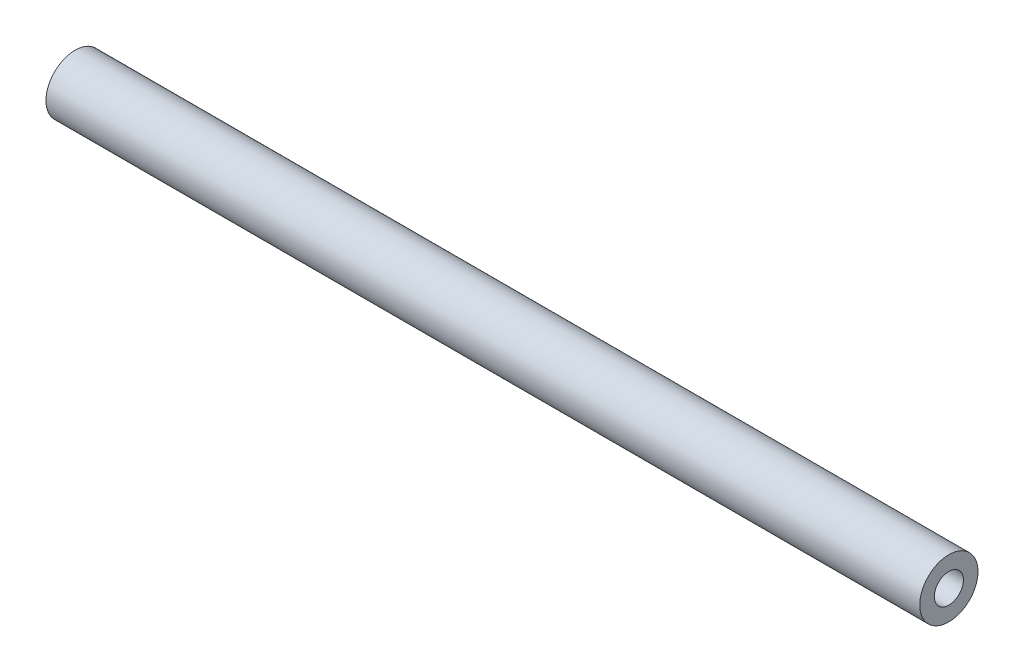
SolidWorks part; units mm, degrees
ref_plane "Front Plane" through (0, 0, 0) normal (0, 0, 1) x (1, 0, 0)
ref_plane "Top Plane" through (0, 0, 0) normal (0, 1, 0) x (1, 0, 0)
ref_plane "Right Plane" through (0, 0, 0) normal (1, 0, 0) x (0, 0, -1)
sketch "Sketch1" plane through (0, 0, 0) normal (1, 0, 0) x (0, 0, -1)
  circle A0 centre (0, 0) radius 2.5
  circle A1 centre (0, 0) radius 5
  dimension "D1" = 5
  dimension "D2" = 10
extrude "Boss-Extrude1" add sketch "Sketch1" along normal mid plane 150
